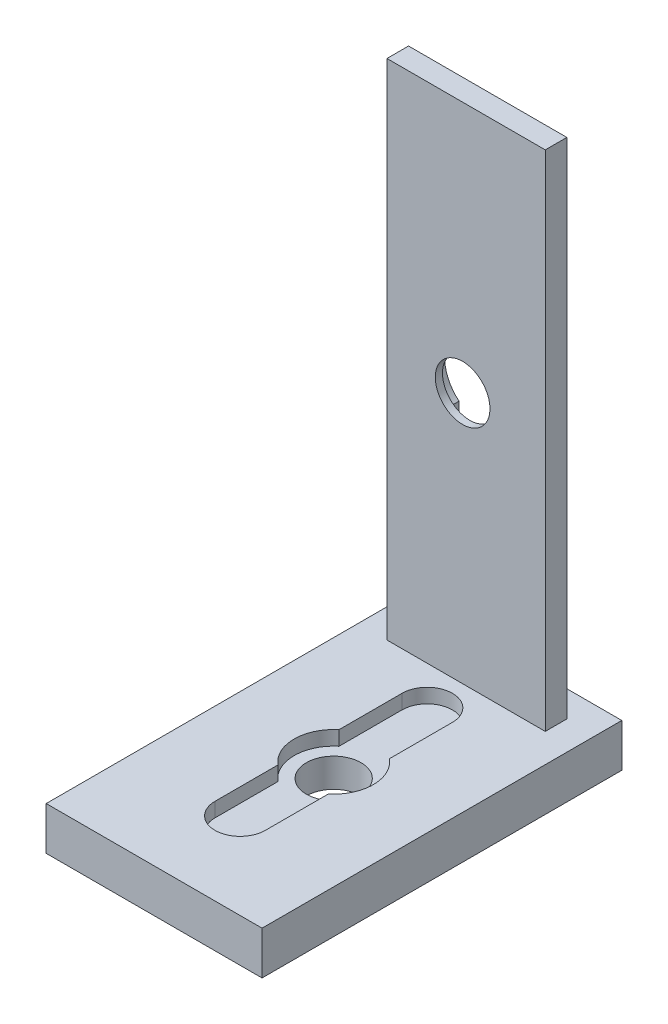
SolidWorks part; units mm, degrees
ref_plane "前视基准面" through (0, 0, 0) normal (0, 0, 1) x (1, 0, 0)
ref_plane "上视基准面" through (0, 0, 0) normal (0, 1, 0) x (1, 0, 0)
ref_plane "右视基准面" through (0, 0, 0) normal (1, 0, 0) x (0, 0, -1)
sketch "草图1" plane through (0, 0, 0) normal (0, 1, 0) x (1, 0, 0)
  line L1 (0, 0) -> (15, 0)
  line L2 (0, 0) -> (0, -25)
  line L3 (0, -25) -> (15, -25)
  line L4 (15, 0) -> (15, -25)
  dimension "D1" = 25
  dimension "D2" = 15
extrude "凸台-拉伸1" add sketch "草图1" along normal blind 3
sketch "草图2" plane through (0, 3, 0) normal (0, 1, 0) x (1, 0, 0)
  line L0 (9.2293, -6) -> (9.2293, -10.3787)
  line L1 (5.7293, -6) -> (5.7293, -10.3787)
  line L2 (9.2293, -14.6213) -> (9.2293, -19)
  line L3 (5.7293, -14.6213) -> (5.7293, -19)
  arc A0 (9.2293, -6) -> (5.7293, -6) centre (7.4793, -6) ccw
  arc A1 (5.7293, -19) -> (9.2293, -19) centre (7.4793, -19) ccw
  arc A2 (5.7293, -10.3787) -> (5.7293, -14.6213) centre (7.4793, -12.5) ccw
  arc A3 (9.2293, -14.6213) -> (9.2293, -10.3787) centre (7.4793, -12.5) ccw
  dimension "D1" = 3.5
  dimension "D3" = 5.5
  dimension "D2" = 13
  dimension "D4" = 6.5
  dimension "D5" = 6.5
extrude "切除-拉伸1" cut sketch "草图2" against normal blind 1
sketch "草图3" plane through (0, 2, 0) normal (0, 1, 0) x (1, 0, 0)
  circle A0 centre (7.4793, -12.5) radius 1.9
  arc A1 (9.2293, -6) -> (5.7293, -6) centre (7.4793, -6) ccw construction
  arc A2 (9.2293, -14.6213) -> (9.2293, -10.3787) centre (7.4793, -12.5) ccw construction
  dimension "D1" = 3.8
  dimension "D2" = 6.5
  dimension "D3" = 0
extrude "切除-拉伸2" cut sketch "草图3" against normal through all
sketch "草图4" plane through (0, 3, 0) normal (0, 1, 0) x (1, 0, 0)
  line L0 (15, -25) -> (15, 0) construction
  line L1 (13.0005, -1.8199) -> (2, -1.8199)
  line L2 (13.0005, -1.8199) -> (13.0005, -3.3199)
  line L3 (13.0005, -3.3199) -> (2, -3.3199)
  line L4 (2, -1.8199) -> (2, -3.3199)
  line L5 (0, 0) -> (0, -25) construction
  dimension "D1" = 1.5
  dimension "D2" = 1.9995
  dimension "D3" = 2
extrude "凸台-拉伸2" add sketch "草图4" along normal blind 35
sketch "草图5" plane through (0, 0, 1.8199) normal (0, 0, -1) x (-1, 0, 0)
  line L0 (-9.0088, 14) -> (-9.0088, 18.3787)
  line L1 (-5.5088, 14) -> (-5.5088, 18.3787)
  line L2 (-13.0005, 3) -> (-2, 3) construction
  line L3 (-13.0005, 38) -> (-2, 38) construction
  line L4 (-9.0088, 22.6213) -> (-9.0088, 27)
  line L5 (-5.5088, 22.6213) -> (-5.5088, 27)
  arc A0 (-9.0088, 14) -> (-5.5088, 14) centre (-7.2588, 14) ccw
  arc A1 (-5.5088, 27) -> (-9.0088, 27) centre (-7.2588, 27) ccw
  arc A2 (-5.5088, 18.3787) -> (-5.5088, 22.6213) centre (-7.2588, 20.5) ccw
  arc A3 (-9.0088, 22.6213) -> (-9.0088, 18.3787) centre (-7.2588, 20.5) ccw
  point P1 (0, 0)
  point P3 (0, 0)
  point P14 (-7.1158, 20.5)
  point P15 (-6.7267, 22.7502)
  point P16 (-6.4263, 22.5734)
  point P17 (-7.1158, 20.5)
  point P21 (-7.1158, 20.5)
  point P22 (-7.097, 20.5)
  point P23 (-7.097, 20.5)
  dimension "D1" = 3.5
  dimension "D4" = 11
  dimension "D5" = 11
  dimension "D8" = 6.5
extrude "切除-拉伸3" cut sketch "草图5" against normal blind 1
sketch "草图6" plane through (0, 0, 2.8199) normal (0, 0, -1) x (-1, 0, 0)
  circle A0 centre (-7.2588, 20.5) radius 1.9
  arc A1 (-9.0088, 22.6213) -> (-9.0088, 18.3787) centre (-7.2588, 20.5) ccw construction
  dimension "D1" = 0
  dimension "D2" = 3.8
extrude "切除-拉伸4" cut sketch "草图6" against normal blind 10
